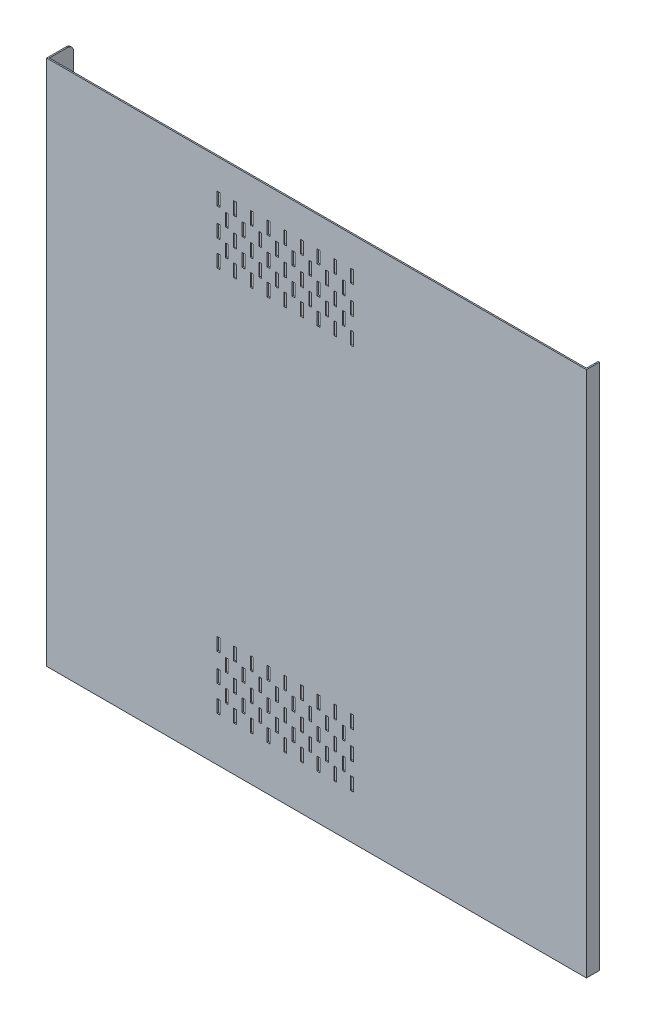
SolidWorks part; units mm, degrees
ref_plane "Piano frontale" through (0, 0, 0) normal (0, 0, 1) x (1, 0, 0)
ref_plane "Piano superiore" through (0, 0, 0) normal (0, 1, 0) x (1, 0, 0)
ref_plane "Piano destro" through (0, 0, 0) normal (1, 0, 0) x (0, 0, -1)
sketch "Schizzo1" plane through (0, 0, 0) normal (0, 0, 1) x (1, 0, 0)
  line L1 (210, -205) -> (-210, -205)
  line L2 (210, -205) -> (210, 205)
  line L3 (210, 205) -> (-210, 205)
  line L4 (-210, -205) -> (-210, 205)
  line L5 (210, -205) -> (-210, 205) construction
  line L6 (210, 205) -> (-210, -205) construction
  point P0 (0, 0)
  dimension "D1" = 420
  dimension "D2" = 410
extrude "Estrusione-Estrusione1" add sketch "Schizzo1" along normal blind 1
sketch "Schizzo2" plane through (0, 0, 1) normal (0, 0, 1) x (1, 0, 0)
  line L0 (-80, 185) -> (30, 185) construction
  line L1 (30, 185) -> (30, 125) construction
  line L2 (30, 125) -> (-80, 125) construction
  line L3 (-80, 125) -> (-80, 185) construction
  line L4 (-80, -115) -> (30, -115) construction
  line L5 (30, -115) -> (30, -175) construction
  line L6 (30, -175) -> (-80, -175) construction
  line L7 (-80, -175) -> (-80, -115) construction
  line L8 (210, 205) -> (-210, 205) construction
  line L9 (-210, 205) -> (-210, -205) construction
  line L10 (-210, -205) -> (210, -205) construction
  line L11 (-64.5071, 181.5959) -> (-62.3389, 181.5959)
  line L12 (-77.5071, 181.5959) -> (-75.3389, 181.5959)
  line L13 (-77.5071, 181.5959) -> (-77.5071, 171.5959)
  line L14 (-77.5071, 171.5959) -> (-75.3389, 171.5959)
  line L15 (-75.3389, 181.5959) -> (-75.3389, 171.5959)
  line L16 (-64.5071, 181.5959) -> (-64.5071, 171.5959)
  line L17 (-64.5071, 171.5959) -> (-62.3389, 171.5959)
  line L18 (-62.3389, 181.5959) -> (-62.3389, 171.5959)
  line L19 (-51.5071, 181.5959) -> (-49.3389, 181.5959)
  line L20 (-51.5071, 181.5959) -> (-51.5071, 171.5959)
  line L21 (-51.5071, 171.5959) -> (-49.3389, 171.5959)
  line L22 (-49.3389, 181.5959) -> (-49.3389, 171.5959)
  line L23 (-38.5071, 181.5959) -> (-36.3389, 181.5959)
  line L24 (-38.5071, 181.5959) -> (-38.5071, 171.5959)
  line L25 (-38.5071, 171.5959) -> (-36.3389, 171.5959)
  line L26 (-36.3389, 181.5959) -> (-36.3389, 171.5959)
  line L27 (-25.5071, 181.5959) -> (-23.3389, 181.5959)
  line L28 (-25.5071, 181.5959) -> (-25.5071, 171.5959)
  line L29 (-25.5071, 171.5959) -> (-23.3389, 171.5959)
  line L30 (-23.3389, 181.5959) -> (-23.3389, 171.5959)
  line L31 (-12.5071, 181.5959) -> (-10.3389, 181.5959)
  line L32 (-12.5071, 181.5959) -> (-12.5071, 171.5959)
  line L33 (-12.5071, 171.5959) -> (-10.3389, 171.5959)
  line L34 (-10.3389, 181.5959) -> (-10.3389, 171.5959)
  line L35 (0.4929, 181.5959) -> (2.6611, 181.5959)
  line L36 (0.4929, 181.5959) -> (0.4929, 171.5959)
  line L37 (0.4929, 171.5959) -> (2.6611, 171.5959)
  line L38 (2.6611, 181.5959) -> (2.6611, 171.5959)
  line L39 (13.4929, 181.5959) -> (15.6611, 181.5959)
  line L40 (13.4929, 181.5959) -> (13.4929, 171.5959)
  line L41 (13.4929, 171.5959) -> (15.6611, 171.5959)
  line L42 (15.6611, 181.5959) -> (15.6611, 171.5959)
  line L43 (26.4929, 181.5959) -> (28.6611, 181.5959)
  line L44 (26.4929, 181.5959) -> (26.4929, 171.5959)
  line L45 (26.4929, 171.5959) -> (28.6611, 171.5959)
  line L46 (28.6611, 181.5959) -> (28.6611, 171.5959)
  line L47 (-75.3389, 159.9706) -> (-75.3389, 149.9706)
  line L48 (-64.5071, 159.9706) -> (-62.3389, 159.9706)
  line L49 (26.4929, 159.9706) -> (26.4929, 149.9706)
  line L50 (-12.5071, 149.9706) -> (-10.3389, 149.9706)
  line L51 (-64.5071, 149.9706) -> (-62.3389, 149.9706)
  line L52 (-77.5071, 159.9706) -> (-75.3389, 159.9706)
  line L53 (-23.3389, 159.9706) -> (-23.3389, 149.9706)
  line L54 (15.6611, 159.9706) -> (15.6611, 149.9706)
  line L55 (-12.5071, 159.9706) -> (-12.5071, 149.9706)
  line L56 (-62.3389, 159.9706) -> (-62.3389, 149.9706)
  line L57 (-25.5071, 149.9706) -> (-23.3389, 149.9706)
  line L58 (-51.5071, 159.9706) -> (-51.5071, 149.9706)
  line L59 (-12.5071, 159.9706) -> (-10.3389, 159.9706)
  line L60 (26.4929, 149.9706) -> (28.6611, 149.9706)
  line L61 (-38.5071, 159.9706) -> (-38.5071, 149.9706)
  line L62 (13.4929, 159.9706) -> (15.6611, 159.9706)
  line L63 (-51.5071, 149.9706) -> (-49.3389, 149.9706)
  line L64 (26.4929, 159.9706) -> (28.6611, 159.9706)
  line L65 (-10.3389, 159.9706) -> (-10.3389, 149.9706)
  line L66 (-38.5071, 159.9706) -> (-36.3389, 159.9706)
  line L67 (-36.3389, 159.9706) -> (-36.3389, 149.9706)
  line L68 (13.4929, 159.9706) -> (13.4929, 149.9706)
  line L69 (-25.5071, 159.9706) -> (-23.3389, 159.9706)
  line L70 (28.6611, 159.9706) -> (28.6611, 149.9706)
  line L71 (-77.5071, 159.9706) -> (-77.5071, 149.9706)
  line L72 (0.4929, 159.9706) -> (0.4929, 149.9706)
  line L73 (2.6611, 159.9706) -> (2.6611, 149.9706)
  line L74 (-51.5071, 159.9706) -> (-49.3389, 159.9706)
  line L75 (0.4929, 149.9706) -> (2.6611, 149.9706)
  line L76 (0.4929, 159.9706) -> (2.6611, 159.9706)
  line L77 (-38.5071, 149.9706) -> (-36.3389, 149.9706)
  line L78 (-49.3389, 159.9706) -> (-49.3389, 149.9706)
  line L79 (-77.5071, 149.9706) -> (-75.3389, 149.9706)
  line L80 (-25.5071, 159.9706) -> (-25.5071, 149.9706)
  line L81 (-64.5071, 159.9706) -> (-64.5071, 149.9706)
  line L82 (13.4929, 149.9706) -> (15.6611, 149.9706)
  line L83 (-77.5071, 139.7431) -> (-77.5071, 129.7431)
  line L84 (13.4929, 139.7431) -> (13.4929, 129.7431)
  line L85 (-77.5071, 139.7431) -> (-75.3389, 139.7431)
  line L86 (-38.5071, 139.7431) -> (-38.5071, 129.7431)
  line L87 (0.4929, 139.7431) -> (0.4929, 129.7431)
  line L88 (2.6611, 139.7431) -> (2.6611, 129.7431)
  line L89 (-64.5071, 139.7431) -> (-64.5071, 129.7431)
  line L90 (-12.5071, 139.7431) -> (-12.5071, 129.7431)
  line L91 (-12.5071, 129.7431) -> (-10.3389, 129.7431)
  line L92 (0.4929, 129.7431) -> (2.6611, 129.7431)
  line L93 (-49.3389, 139.7431) -> (-49.3389, 129.7431)
  line L94 (-51.5071, 129.7431) -> (-49.3389, 129.7431)
  line L95 (13.4929, 129.7431) -> (15.6611, 129.7431)
  line L96 (-38.5071, 129.7431) -> (-36.3389, 129.7431)
  line L97 (-25.5071, 139.7431) -> (-25.5071, 129.7431)
  line L98 (26.4929, 129.7431) -> (28.6611, 129.7431)
  line L99 (-36.3389, 139.7431) -> (-36.3389, 129.7431)
  line L100 (15.6611, 139.7431) -> (15.6611, 129.7431)
  line L101 (-64.5071, 139.7431) -> (-62.3389, 139.7431)
  line L102 (-51.5071, 139.7431) -> (-51.5071, 129.7431)
  line L103 (-62.3389, 139.7431) -> (-62.3389, 129.7431)
  line L104 (28.6611, 139.7431) -> (28.6611, 129.7431)
  line L105 (-25.5071, 129.7431) -> (-23.3389, 129.7431)
  line L106 (26.4929, 139.7431) -> (26.4929, 129.7431)
  line L107 (-10.3389, 139.7431) -> (-10.3389, 129.7431)
  line L108 (-75.3389, 139.7431) -> (-75.3389, 129.7431)
  line L109 (-23.3389, 139.7431) -> (-23.3389, 129.7431)
  line L110 (-77.5071, 129.7431) -> (-75.3389, 129.7431)
  line L111 (-64.5071, 129.7431) -> (-62.3389, 129.7431)
  line L112 (28.6611, 139.7431) -> (26.4929, 139.7431)
  line L113 (15.6611, 139.7431) -> (13.4929, 139.7431)
  line L114 (2.6611, 139.7431) -> (0.4929, 139.7431)
  line L115 (-10.3389, 139.7431) -> (-12.5071, 139.7431)
  line L116 (-23.3389, 139.7431) -> (-25.5071, 139.7431)
  line L117 (-36.3389, 139.7431) -> (-38.5071, 139.7431)
  line L118 (-49.3389, 139.7431) -> (-51.5071, 139.7431)
  line L119 (-31.9866, 170.6992) -> (-29.8184, 170.6992)
  line L120 (-57.9866, 170.6992) -> (-57.9866, 160.6992)
  line L121 (20.0134, 160.6992) -> (22.1816, 160.6992)
  line L122 (-5.9866, 170.6992) -> (-3.8184, 170.6992)
  line L123 (-29.8184, 170.6992) -> (-29.8184, 160.6992)
  line L124 (-18.9866, 170.6992) -> (-18.9866, 160.6992)
  line L125 (7.0134, 170.6992) -> (7.0134, 160.6992)
  line L126 (22.1816, 170.6992) -> (22.1816, 160.6992)
  line L127 (-5.9866, 170.6992) -> (-5.9866, 160.6992)
  line L128 (20.0134, 170.6992) -> (22.1816, 170.6992)
  line L129 (-44.9866, 170.6992) -> (-42.8184, 170.6992)
  line L130 (-44.9866, 160.6992) -> (-42.8184, 160.6992)
  line L131 (-18.9866, 160.6992) -> (-16.8184, 160.6992)
  line L132 (-55.8184, 170.6992) -> (-55.8184, 160.6992)
  line L133 (-70.9866, 170.6992) -> (-70.9866, 160.6992)
  line L134 (-70.9866, 170.6992) -> (-68.8184, 170.6992)
  line L135 (20.0134, 170.6992) -> (20.0134, 160.6992)
  line L136 (-57.9866, 160.6992) -> (-55.8184, 160.6992)
  line L137 (-3.8184, 170.6992) -> (-3.8184, 160.6992)
  line L138 (-57.9866, 170.6992) -> (-55.8184, 170.6992)
  line L139 (-31.9866, 160.6992) -> (-29.8184, 160.6992)
  line L140 (-42.8184, 170.6992) -> (-42.8184, 160.6992)
  line L141 (-31.9866, 170.6992) -> (-31.9866, 160.6992)
  line L142 (9.1816, 170.6992) -> (9.1816, 160.6992)
  line L143 (-68.8184, 170.6992) -> (-68.8184, 160.6992)
  line L144 (-18.9866, 170.6992) -> (-16.8184, 170.6992)
  line L145 (-5.9866, 160.6992) -> (-3.8184, 160.6992)
  line L146 (7.0134, 160.6992) -> (9.1816, 160.6992)
  line L147 (-70.9866, 160.6992) -> (-68.8184, 160.6992)
  line L148 (-44.9866, 170.6992) -> (-44.9866, 160.6992)
  line L149 (7.0134, 170.6992) -> (9.1816, 170.6992)
  line L150 (-16.8184, 170.6992) -> (-16.8184, 160.6992)
  line L151 (-31.9866, 139.9706) -> (-29.8184, 139.9706)
  line L152 (-57.9866, 149.9706) -> (-55.8184, 149.9706)
  line L153 (-31.9866, 149.9706) -> (-31.9866, 139.9706)
  line L154 (20.0134, 149.9706) -> (20.0134, 139.9706)
  line L155 (-44.9866, 139.9706) -> (-42.8184, 139.9706)
  line L156 (-16.8184, 149.9706) -> (-16.8184, 139.9706)
  line L157 (-70.9866, 149.9706) -> (-68.8184, 149.9706)
  line L158 (-29.8184, 149.9706) -> (-29.8184, 139.9706)
  line L159 (-57.9866, 149.9706) -> (-57.9866, 139.9706)
  line L160 (-70.9866, 139.9706) -> (-68.8184, 139.9706)
  line L161 (7.0134, 149.9706) -> (9.1816, 149.9706)
  line L162 (-18.9866, 149.9706) -> (-16.8184, 149.9706)
  line L163 (20.0134, 149.9706) -> (22.1816, 149.9706)
  line L164 (9.1816, 149.9706) -> (9.1816, 139.9706)
  line L165 (7.0134, 149.9706) -> (7.0134, 139.9706)
  line L166 (7.0134, 139.9706) -> (9.1816, 139.9706)
  line L167 (-18.9866, 149.9706) -> (-18.9866, 139.9706)
  line L168 (-44.9866, 149.9706) -> (-42.8184, 149.9706)
  line L169 (-3.8184, 149.9706) -> (-3.8184, 139.9706)
  line L170 (-70.9866, 149.9706) -> (-70.9866, 139.9706)
  line L171 (20.0134, 139.9706) -> (22.1816, 139.9706)
  line L172 (-5.9866, 149.9706) -> (-3.8184, 149.9706)
  line L173 (-31.9866, 149.9706) -> (-29.8184, 149.9706)
  line L174 (22.1816, 149.9706) -> (22.1816, 139.9706)
  line L175 (-68.8184, 149.9706) -> (-68.8184, 139.9706)
  line L176 (-5.9866, 149.9706) -> (-5.9866, 139.9706)
  line L177 (-42.8184, 149.9706) -> (-42.8184, 139.9706)
  line L178 (-5.9866, 139.9706) -> (-3.8184, 139.9706)
  line L179 (-57.9866, 139.9706) -> (-55.8184, 139.9706)
  line L180 (-18.9866, 139.9706) -> (-16.8184, 139.9706)
  line L181 (-55.8184, 149.9706) -> (-55.8184, 139.9706)
  line L182 (-44.9866, 149.9706) -> (-44.9866, 139.9706)
  line L183 (-64.5071, -118.5083) -> (-62.3389, -118.5083)
  line L184 (-62.3389, -118.5083) -> (-62.3389, -128.5083)
  line L185 (-36.3389, -118.5083) -> (-36.3389, -128.5083)
  line L186 (0.4929, -140.1336) -> (0.4929, -150.1336)
  line L187 (-51.5071, -140.1336) -> (-49.3389, -140.1336)
  line L188 (0.4929, -160.3612) -> (0.4929, -170.3612)
  line L189 (2.6611, -160.3612) -> (0.4929, -160.3612)
  line L190 (-5.9866, -129.405) -> (-5.9866, -139.405)
  line L191 (7.0134, -139.405) -> (9.1816, -139.405)
  line L192 (20.0134, -150.1336) -> (22.1816, -150.1336)
  line L193 (-55.8184, -150.1336) -> (-55.8184, -160.1336)
  line L194 (-77.5071, -170.3612) -> (-75.3389, -170.3612)
  line L195 (-51.5071, -128.5083) -> (-49.3389, -128.5083)
  line L196 (0.4929, -118.5083) -> (0.4929, -128.5083)
  line L197 (15.6611, -140.1336) -> (15.6611, -150.1336)
  line L198 (26.4929, -140.1336) -> (28.6611, -140.1336)
  line L199 (13.4929, -150.1336) -> (15.6611, -150.1336)
  line L200 (-10.3389, -160.3612) -> (-10.3389, -170.3612)
  line L201 (-5.9866, -129.405) -> (-3.8184, -129.405)
  line L202 (-44.9866, -139.405) -> (-42.8184, -139.405)
  line L203 (-44.9866, -160.1336) -> (-42.8184, -160.1336)
  line L204 (-44.9866, -150.1336) -> (-42.8184, -150.1336)
  line L205 (-77.5071, -150.1336) -> (-75.3389, -150.1336)
  line L206 (-38.5071, -140.1336) -> (-36.3389, -140.1336)
  line L207 (0.4929, -150.1336) -> (2.6611, -150.1336)
  line L208 (-12.5071, -170.3612) -> (-10.3389, -170.3612)
  line L209 (26.4929, -170.3612) -> (28.6611, -170.3612)
  line L210 (7.0134, -129.405) -> (7.0134, -139.405)
  line L211 (-31.9866, -129.405) -> (-31.9866, -139.405)
  line L212 (7.0134, -150.1336) -> (7.0134, -160.1336)
  line L213 (-70.9866, -150.1336) -> (-70.9866, -160.1336)
  line L214 (-77.5071, -160.3612) -> (-75.3389, -160.3612)
  line L215 (-25.5071, -150.1336) -> (-23.3389, -150.1336)
  line L216 (-36.3389, -140.1336) -> (-36.3389, -150.1336)
  line L217 (-38.5071, -150.1336) -> (-36.3389, -150.1336)
  line L218 (26.4929, -160.3612) -> (26.4929, -170.3612)
  line L219 (-49.3389, -160.3612) -> (-51.5071, -160.3612)
  line L220 (9.1816, -129.405) -> (9.1816, -139.405)
  line L221 (-57.9866, -150.1336) -> (-55.8184, -150.1336)
  line L222 (-5.9866, -150.1336) -> (-3.8184, -150.1336)
  line L223 (-5.9866, -150.1336) -> (-5.9866, -160.1336)
  line L224 (-77.5071, -128.5083) -> (-75.3389, -128.5083)
  line L225 (-12.5071, -128.5083) -> (-10.3389, -128.5083)
  line L226 (-23.3389, -140.1336) -> (-23.3389, -150.1336)
  line L227 (-51.5071, -150.1336) -> (-49.3389, -150.1336)
  line L228 (-38.5071, -170.3612) -> (-36.3389, -170.3612)
  line L229 (-64.5071, -160.3612) -> (-62.3389, -160.3612)
  line L230 (-57.9866, -139.405) -> (-55.8184, -139.405)
  line L231 (-3.8184, -129.405) -> (-3.8184, -139.405)
  line L232 (-31.9866, -160.1336) -> (-29.8184, -160.1336)
  line L233 (-5.9866, -160.1336) -> (-3.8184, -160.1336)
  line L234 (-51.5071, -118.5083) -> (-51.5071, -128.5083)
  line L235 (-38.5071, -128.5083) -> (-36.3389, -128.5083)
  line L236 (-77.5071, -140.1336) -> (-75.3389, -140.1336)
  line L237 (-25.5071, -140.1336) -> (-23.3389, -140.1336)
  line L238 (15.6611, -160.3612) -> (15.6611, -170.3612)
  line L239 (-31.9866, -129.405) -> (-29.8184, -129.405)
  line L240 (-18.9866, -139.405) -> (-16.8184, -139.405)
  line L241 (-70.9866, -139.405) -> (-68.8184, -139.405)
  line L242 (-68.8184, -150.1336) -> (-68.8184, -160.1336)
  line L243 (-44.9866, -150.1336) -> (-44.9866, -160.1336)
  line L244 (-49.3389, -118.5083) -> (-49.3389, -128.5083)
  line L245 (-25.5071, -118.5083) -> (-25.5071, -128.5083)
  line L246 (28.6611, -118.5083) -> (28.6611, -128.5083)
  line L247 (-51.5071, -140.1336) -> (-51.5071, -150.1336)
  line L248 (13.4929, -160.3612) -> (13.4929, -170.3612)
  line L249 (-75.3389, -160.3612) -> (-75.3389, -170.3612)
  line L250 (-23.3389, -160.3612) -> (-25.5071, -160.3612)
  line L251 (-36.3389, -160.3612) -> (-38.5071, -160.3612)
  line L252 (-16.8184, -150.1336) -> (-16.8184, -160.1336)
  line L253 (-18.9866, -160.1336) -> (-16.8184, -160.1336)
  line L254 (-77.5071, -118.5083) -> (-77.5071, -128.5083)
  line L255 (-25.5071, -118.5083) -> (-23.3389, -118.5083)
  line L256 (15.6611, -118.5083) -> (15.6611, -128.5083)
  line L257 (13.4929, -140.1336) -> (13.4929, -150.1336)
  line L258 (-38.5071, -160.3612) -> (-38.5071, -170.3612)
  line L259 (-12.5071, -160.3612) -> (-12.5071, -170.3612)
  line L260 (0.4929, -170.3612) -> (2.6611, -170.3612)
  line L261 (20.0134, -129.405) -> (20.0134, -139.405)
  line L262 (-68.8184, -129.405) -> (-68.8184, -139.405)
  line L263 (7.0134, -160.1336) -> (9.1816, -160.1336)
  line L264 (-23.3389, -118.5083) -> (-23.3389, -128.5083)
  line L265 (-10.3389, -118.5083) -> (-10.3389, -128.5083)
  line L266 (-64.5071, -150.1336) -> (-62.3389, -150.1336)
  line L267 (-12.5071, -140.1336) -> (-10.3389, -140.1336)
  line L268 (-49.3389, -140.1336) -> (-49.3389, -150.1336)
  line L269 (-25.5071, -160.3612) -> (-25.5071, -170.3612)
  line L270 (-10.3389, -160.3612) -> (-12.5071, -160.3612)
  line L271 (20.0134, -139.405) -> (22.1816, -139.405)
  line L272 (-31.9866, -150.1336) -> (-31.9866, -160.1336)
  line L273 (20.0134, -160.1336) -> (22.1816, -160.1336)
  line L274 (-64.5071, -118.5083) -> (-64.5071, -128.5083)
  line L275 (0.4929, -128.5083) -> (2.6611, -128.5083)
  line L276 (2.6611, -118.5083) -> (2.6611, -128.5083)
  line L277 (26.4929, -118.5083) -> (26.4929, -128.5083)
  line L278 (26.4929, -128.5083) -> (28.6611, -128.5083)
  line L279 (-51.5071, -160.3612) -> (-51.5071, -170.3612)
  line L280 (-64.5071, -170.3612) -> (-62.3389, -170.3612)
  line L281 (-44.9866, -129.405) -> (-42.8184, -129.405)
  line L282 (-70.9866, -129.405) -> (-70.9866, -139.405)
  line L283 (-57.9866, -150.1336) -> (-57.9866, -160.1336)
  line L284 (-38.5071, -118.5083) -> (-38.5071, -128.5083)
  line L285 (-75.3389, -140.1336) -> (-75.3389, -150.1336)
  line L286 (2.6611, -140.1336) -> (2.6611, -150.1336)
  line L287 (28.6611, -160.3612) -> (28.6611, -170.3612)
  line L288 (-55.8184, -129.405) -> (-55.8184, -139.405)
  line L289 (-31.9866, -139.405) -> (-29.8184, -139.405)
  line L290 (-44.9866, -129.405) -> (-44.9866, -139.405)
  line L291 (9.1816, -150.1336) -> (9.1816, -160.1336)
  line L292 (-77.5071, -118.5083) -> (-75.3389, -118.5083)
  line L293 (-38.5071, -140.1336) -> (-38.5071, -150.1336)
  line L294 (-10.3389, -140.1336) -> (-10.3389, -150.1336)
  line L295 (13.4929, -170.3612) -> (15.6611, -170.3612)
  line L296 (-36.3389, -160.3612) -> (-36.3389, -170.3612)
  line L297 (15.6611, -160.3612) -> (13.4929, -160.3612)
  line L298 (7.0134, -129.405) -> (9.1816, -129.405)
  line L299 (-70.9866, -150.1336) -> (-68.8184, -150.1336)
  line L300 (-31.9866, -150.1336) -> (-29.8184, -150.1336)
  line L301 (-42.8184, -150.1336) -> (-42.8184, -160.1336)
  line L302 (26.4929, -140.1336) -> (26.4929, -150.1336)
  line L303 (28.6611, -140.1336) -> (28.6611, -150.1336)
  line L304 (-51.5071, -170.3612) -> (-49.3389, -170.3612)
  line L305 (20.0134, -129.405) -> (22.1816, -129.405)
  line L306 (-57.9866, -129.405) -> (-55.8184, -129.405)
  line L307 (-18.9866, -129.405) -> (-16.8184, -129.405)
  line L308 (-18.9866, -150.1336) -> (-18.9866, -160.1336)
  line L309 (-57.9866, -160.1336) -> (-55.8184, -160.1336)
  line L310 (-75.3389, -118.5083) -> (-75.3389, -128.5083)
  line L311 (-51.5071, -118.5083) -> (-49.3389, -118.5083)
  line L312 (-38.5071, -118.5083) -> (-36.3389, -118.5083)
  line L313 (-12.5071, -118.5083) -> (-10.3389, -118.5083)
  line L314 (0.4929, -118.5083) -> (2.6611, -118.5083)
  line L315 (-64.5071, -140.1336) -> (-62.3389, -140.1336)
  line L316 (26.4929, -150.1336) -> (28.6611, -150.1336)
  line L317 (-25.5071, -140.1336) -> (-25.5071, -150.1336)
  line L318 (-62.3389, -160.3612) -> (-62.3389, -170.3612)
  line L319 (22.1816, -129.405) -> (22.1816, -139.405)
  line L320 (-5.9866, -139.405) -> (-3.8184, -139.405)
  line L321 (20.0134, -150.1336) -> (20.0134, -160.1336)
  line L322 (-70.9866, -160.1336) -> (-68.8184, -160.1336)
  line L323 (-18.9866, -150.1336) -> (-16.8184, -150.1336)
  line L324 (-77.5071, -140.1336) -> (-77.5071, -150.1336)
  line L325 (-77.5071, -160.3612) -> (-77.5071, -170.3612)
  line L326 (-64.5071, -128.5083) -> (-62.3389, -128.5083)
  line L327 (13.4929, -128.5083) -> (15.6611, -128.5083)
  line L328 (-12.5071, -140.1336) -> (-12.5071, -150.1336)
  line L329 (-64.5071, -140.1336) -> (-64.5071, -150.1336)
  line L330 (2.6611, -160.3612) -> (2.6611, -170.3612)
  line L331 (-64.5071, -160.3612) -> (-64.5071, -170.3612)
  line L332 (-29.8184, -129.405) -> (-29.8184, -139.405)
  line L333 (-42.8184, -129.405) -> (-42.8184, -139.405)
  line L334 (7.0134, -150.1336) -> (9.1816, -150.1336)
  line L335 (-3.8184, -150.1336) -> (-3.8184, -160.1336)
  line L336 (-25.5071, -128.5083) -> (-23.3389, -128.5083)
  line L337 (13.4929, -118.5083) -> (15.6611, -118.5083)
  line L338 (26.4929, -118.5083) -> (28.6611, -118.5083)
  line L339 (-12.5071, -150.1336) -> (-10.3389, -150.1336)
  line L340 (0.4929, -140.1336) -> (2.6611, -140.1336)
  line L341 (-25.5071, -170.3612) -> (-23.3389, -170.3612)
  line L342 (-57.9866, -129.405) -> (-57.9866, -139.405)
  line L343 (-18.9866, -129.405) -> (-18.9866, -139.405)
  line L344 (-16.8184, -129.405) -> (-16.8184, -139.405)
  line L345 (22.1816, -150.1336) -> (22.1816, -160.1336)
  line L346 (-12.5071, -118.5083) -> (-12.5071, -128.5083)
  line L347 (13.4929, -118.5083) -> (13.4929, -128.5083)
  line L348 (-62.3389, -140.1336) -> (-62.3389, -150.1336)
  line L349 (13.4929, -140.1336) -> (15.6611, -140.1336)
  line L350 (-49.3389, -160.3612) -> (-49.3389, -170.3612)
  line L351 (-23.3389, -160.3612) -> (-23.3389, -170.3612)
  line L352 (28.6611, -160.3612) -> (26.4929, -160.3612)
  line L353 (-70.9866, -129.405) -> (-68.8184, -129.405)
  line L354 (-29.8184, -150.1336) -> (-29.8184, -160.1336)
  dimension "D1" = 20
  dimension "D2" = 60
  dimension "D3" = 110
  dimension "D4" = 130
  dimension "D5" = 110
  dimension "D6" = 60
  dimension "D7" = 30
  dimension "D8" = 130
  dimension "D9" = 10
  dimension "D11" = 10
  dimension "D10" = 9
extrude "Taglio-Estrusione1" cut sketch "Schizzo2" against normal blind 1
sketch "Schizzo3" plane through (-210, 0, 0) normal (-1, 0, 0) x (0, 0, 1)
  line L0 (1, 205) -> (-14, 205)
  line L1 (-19, 200) -> (-19, 180)
  line L2 (-14, 175) -> (-8, 175)
  line L3 (-8, 175) -> (-8, -205)
  line L4 (-8, -205) -> (1, -205)
  line L5 (1, -205) -> (1, 205)
  arc A0 (-19, 180) -> (-14, 175) centre (-14, 180) ccw
  arc A1 (-14, 205) -> (-19, 200) centre (-14, 200) ccw
  circle A2 centre (-14, 180) radius 2.4212
  point P10 (-19, 175)
  point P13 (-19, 205)
  dimension "D4" = 5
  dimension "D1" = 20
  dimension "D2" = 9
  dimension "D3" = 30
extrude "Estrusione-Estrusione2" add sketch "Schizzo3" against normal blind 1
sketch "Schizzo4" plane through (210, 0, 0) normal (1, 0, 0) x (0, 0, -1)
  line L1 (-1, 205) -> (9, 205)
  line L2 (-1, 205) -> (-1, -205)
  line L3 (-1, -205) -> (9, -205)
  line L4 (9, 205) -> (9, -205)
  dimension "D1" = 0
  dimension "D2" = 10
extrude "Estrusione-Estrusione3" add sketch "Schizzo4" against normal blind 1
